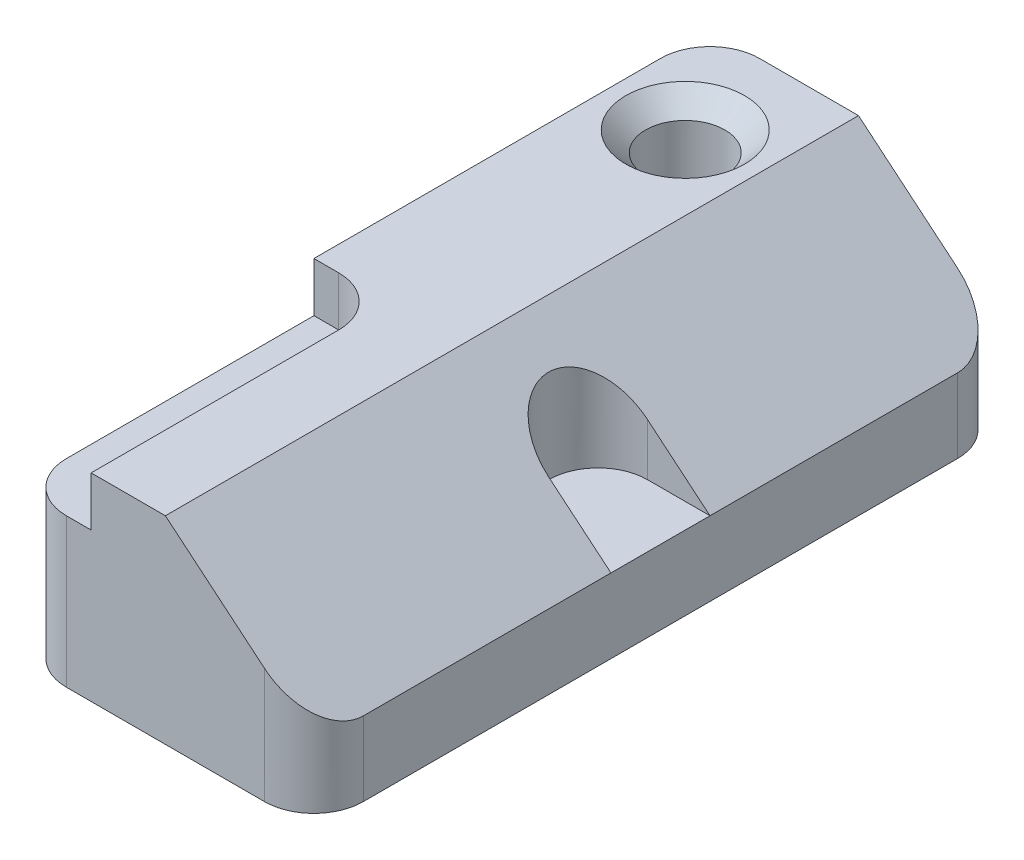
SolidWorks part; units mm, degrees
material "Plain Carbon Steel"
ref_plane "Front Plane" through (0, 0, 0) normal (0, 0, 1) x (1, 0, 0)
ref_plane "Top Plane" through (0, 0, 0) normal (0, 1, 0) x (1, 0, 0)
ref_plane "Right Plane" through (0, 0, 0) normal (1, 0, 0) x (0, 0, -1)
sketch "Sketch1" plane through (0, 0, 0) normal (0, 0, 1) x (1, 0, 0)
  line L0 (0, 0) -> (0, 50.8)
  line L1 (0, 50.8) -> (38.1, 50.8)
  line L2 (38.1, 50.8) -> (76.2, 19.05)
  line L3 (76.2, 19.05) -> (76.2, 0)
  line L4 (76.2, 0) -> (0, 0)
  dimension "D1" = 38.1
  dimension "D2" = 50.8
  dimension "D3" = 19.05
  dimension "D4" = 76.2
extrude "Boss-Extrude1" add sketch "Sketch1" along normal blind 177.8
sketch "Sketch5" plane through (0, 50.8, 0) normal (0, 1, 0) x (1, 0, 0)
  line L0 (0, -177.8) -> (0, 0) construction
  line L2 (38.1, 0) -> (0, 0) construction
  circle A0 centre (19.05, -25.4) radius 10.16
  point P6 (8.0796, 0)
  point P7 (0, 0)
  dimension "D1" = 20.32
  dimension "D2" = 19.05
  dimension "D3" = 25.4
extrude "Cut-Extrude1" cut sketch "Sketch5" against normal through all contours A0
chamfer "Chamfer1" distance 5.08 angle 45 1 edges at (19.05, 50.8, 35.56)
sketch "Sketch6" plane through (0, 50.8, 0) normal (0, 1, 0) x (1, 0, 0)
  line L1 (0, -177.8) -> (19.05, -177.8)
  line L2 (0, -177.8) -> (0, -101.6)
  line L3 (0, -101.6) -> (19.05, -101.6)
  line L4 (19.05, -177.8) -> (19.05, -101.6)
  dimension "D1" = 76.2
  dimension "D2" = 19.05
extrude "Cut-Extrude2" cut sketch "Sketch6" against normal blind 12.7 contours L2 L1 L4 L3
fillet "Fillet1" radius 12.7 1 edges at (19.05, 44.45, 101.6)
sketch "Sketch7" plane through (0, 50.8, 0) normal (0, 1, 0) x (1, 0, 0)
  line L0 (76.2, -76.2) -> (60.198, -76.2)
  line L1 (76.2, -177.8) -> (76.2, 0) construction
  line L2 (76.2, -101.6) -> (60.198, -101.6)
  line L3 (76.2, -88.9) -> (0, -88.9) construction
  line L4 (0, -177.8) -> (0, -101.6) construction
  line L5 (76.2, -76.2) -> (76.2, -101.6)
  arc A0 (60.198, -101.6) -> (60.198, -76.2) centre (60.198, -88.9) cw
  dimension "D1" = 12.7
  dimension "D2" = 16.002
extrude "Cut-Extrude3" cut sketch "Sketch7" against normal up to vertex (31.75 mm away) contours L5 L2 A0 L0
fillet "Fillet2" radius 12.7 4 edges at (0, 25.4, 0) (76.2, 9.525, 0) (76.2, 9.525, 177.8) (0, 19.05, 177.8)
